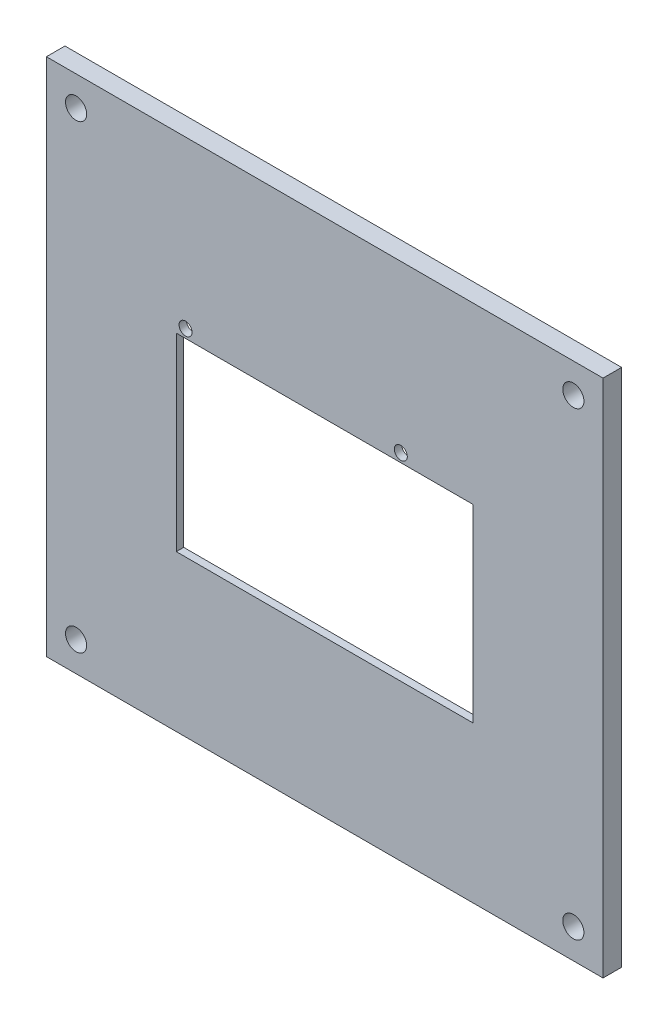
SolidWorks part; units mm, degrees
ref_plane "Front Plane" through (0, 0, 0) normal (0, 0, 1) x (1, 0, 0)
ref_plane "Top Plane" through (0, 0, 0) normal (0, 1, 0) x (1, 0, 0)
ref_plane "Right Plane" through (0, 0, 0) normal (1, 0, 0) x (0, 0, -1)
sketch "Sketch1" plane through (0, 0, 0) normal (0, 0, 1) x (1, 0, 0)
  line L0 (-71.9216, 50.6638) -> (78.0784, 50.6638) construction
  line L1 (-71.9216, 58.6638) -> (78.0784, 58.6638)
  line L2 (-71.9216, 58.6638) -> (-71.9216, -81.3362)
  line L3 (-71.9216, -81.3362) -> (78.0784, -81.3362)
  line L4 (78.0784, 58.6638) -> (78.0784, -81.3362)
  line L5 (-71.9216, -73.3362) -> (78.0784, -73.3362) construction
  line L7 (-36.9216, 11.6638) -> (43.0784, 11.6638)
  line L8 (-36.9216, 11.6638) -> (-36.9216, -39.3362)
  line L9 (-36.9216, -39.3362) -> (43.0784, -39.3362)
  line L10 (43.0784, 11.6638) -> (43.0784, -39.3362)
  circle A0 centre (70.0784, -73.3362) radius 2.85
  circle A1 centre (-63.9216, -73.3362) radius 2.85
  circle A2 centre (-63.9216, 50.6638) radius 2.85
  circle A3 centre (70.0784, 50.6638) radius 2.85
  circle A4 centre (-34.4216, 13.9638) radius 1.75
  circle A5 centre (23.5784, 13.9638) radius 1.75
  dimension "D3" = 5.7
  dimension "D4" = 5.7
  dimension "D5" = 5.7
  dimension "D6" = 5.7
  dimension "D14" = 3.5
  dimension "D15" = 3.5
  dimension "D1" = 140
  dimension "D2" = 150
  dimension "D7" = 8
  dimension "D8" = 8
  dimension "D9" = 8
  dimension "D10" = 8
  dimension "D11" = 8
  dimension "D12" = 80
  dimension "D13" = 51
  dimension "D16" = 58
  dimension "D17" = 2.3
  dimension "D18" = 2.5
  dimension "D19" = 35
  dimension "D20" = 42
extrude "Boss-Extrude1" add sketch "Sketch1" along normal blind 5
sketch "Sketch2" plane through (0, 0, 0) normal (0, 0, -1) x (-1, 0, 0)
  line L0 (36.9216, 11.6638) -> (36.9216, -39.3362) construction
  line L5 (36.9216, -39.3362) -> (-43.0784, -39.3362) construction
  line L6 (-43.0784, -39.3362) -> (-43.0784, 11.6638) construction
  line L7 (-43.0784, 11.6638) -> (36.9216, 11.6638) construction
  line L8 (36.9216, 11.6638) -> (36.9216, -39.3362)
  line L9 (36.9216, -39.3362) -> (-43.0784, -39.3362)
  line L10 (-43.0784, -39.3362) -> (-43.0784, 11.6638)
  line L11 (-43.0784, 11.6638) -> (36.9216, 11.6638)
  line L12 (46.9216, 21.6638) -> (46.9216, -49.3362)
  line L13 (46.9216, -49.3362) -> (-53.0784, -49.3362)
  line L14 (-53.0784, -49.3362) -> (-53.0784, 21.6638)
  line L15 (-53.0784, 21.6638) -> (46.9216, 21.6638)
  dimension "D1" = 10
extrude "Cut-Extrude1" cut sketch "Sketch2" against normal blind 3
equation "\"D4@Sketch1\"=\"D3@Sketch1\""
equation "\"D5@Sketch1\"=\"D4@Sketch1\""
equation "\"D6@Sketch1\"=\"D4@Sketch1\""
equation "\"D9@Sketch1\"=\"D8@Sketch1\""
equation "\"D10@Sketch1\"=\"D7@Sketch1\""
equation "\"D11@Sketch1\"=\"D10@Sketch1\""
